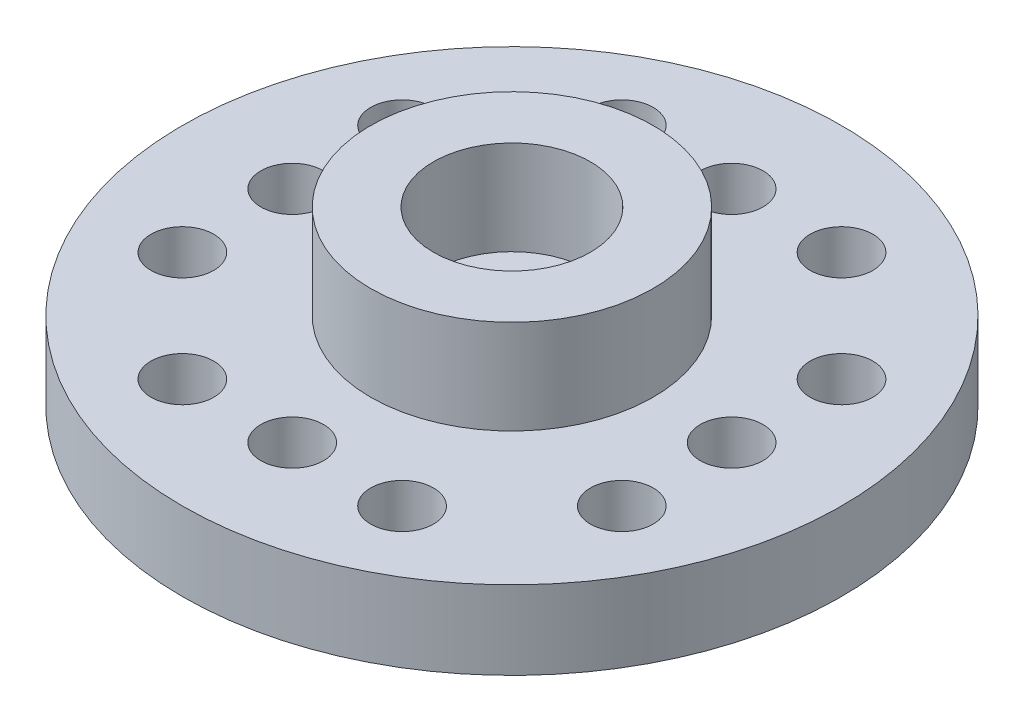
SolidWorks part; units mm, degrees
ref_plane "Front Plane" through (0, 0, 0) normal (0, 0, 1) x (1, 0, 0)
ref_plane "Top Plane" through (0, 0, 0) normal (0, 1, 0) x (1, 0, 0)
ref_plane "Right Plane" through (0, 0, 0) normal (1, 0, 0) x (0, 0, -1)
sketch "Sketch1" plane through (0, 0, 0) normal (0, 1, 0) x (1, 0, 0)
  circle A0 centre (0, 0) radius 10.5
  circle A1 centre (0, 0) radius 1.5
  dimension "D1" = 21
  dimension "D2" = 3
extrude "Boss-Extrude1" add sketch "Sketch1" along normal blind 2.5
sketch "Sketch2" plane through (0, 2.5, 0) normal (0, 1, 0) x (1, 0, 0)
  circle A0 centre (0, 0) radius 4.5
  circle A1 centre (0, 0) radius 2.5
  dimension "D1" = 9
  dimension "D2" = 5
extrude "Boss-Extrude2" add sketch "Sketch2" along normal blind 3
sketch "Sketch3" plane through (0, 0, 0) normal (0, -1, 0) x (1, 0, 0)
  circle A0 centre (-3.5, 7) radius 1
  circle A1 centre (0, 7) radius 1
  circle A2 centre (3.5, 7) radius 1
  circle A3 centre (7, -3.5) radius 1
  circle A4 centre (7, 0) radius 1
  circle A5 centre (7, 3.5) radius 1
  circle A6 centre (-3.5, -7) radius 1
  circle A7 centre (0, -7) radius 1
  circle A8 centre (3.5, -7) radius 1
  circle A9 centre (-7, 3.5) radius 1
  circle A10 centre (-7, 0) radius 1
  circle A11 centre (-7, -3.5) radius 1
  point P28 (0, 0)
  dimension "D4" = 2
  dimension "D1" = 7
  dimension "D2" = 3.5
  dimension "D3" = 3.5
  dimension "D5" = 4
extrude "Cut-Extrude1" cut sketch "Sketch3" against normal up to next
